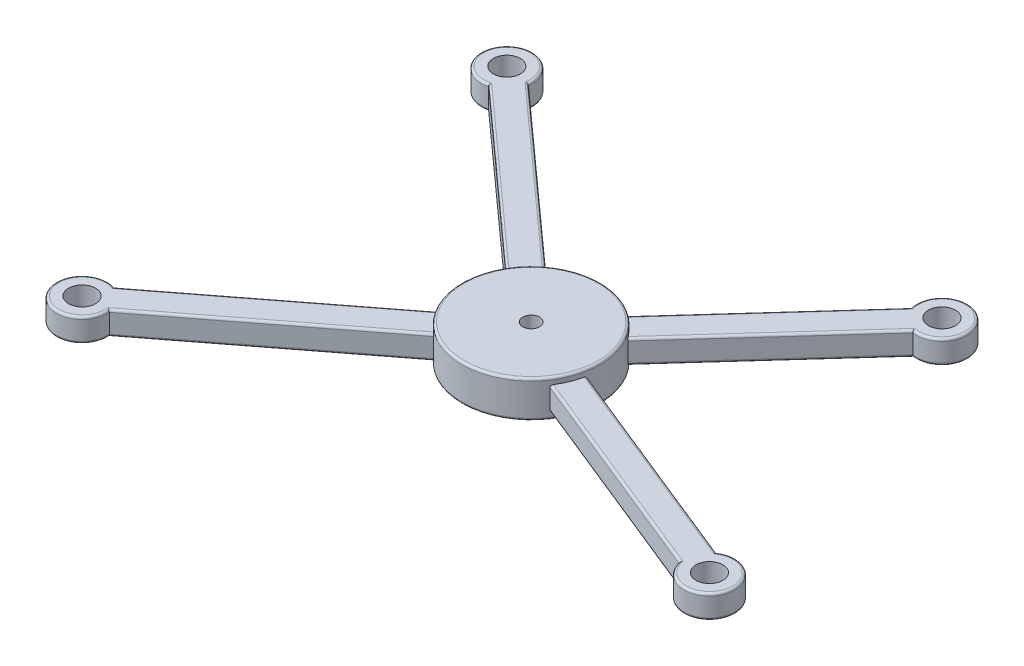
SolidWorks part; units mm, degrees
material "ABS"
ref_plane "Front Plane" through (0, 0, 0) normal (0, 0, 1) x (1, 0, 0)
ref_plane "Top Plane" through (0, 0, 0) normal (0, 1, 0) x (1, 0, 0)
ref_plane "Right Plane" through (0, 0, 0) normal (1, 0, 0) x (0, 0, -1)
sketch "Sketch1" plane through (0, 0, 0) normal (0, 1, 0) x (1, 0, 0)
  line L12 (-46.5941, 45.9944) -> (-0.2219, 4.3139)
  line L13 (36.9296, 45.3443) -> (-0.2219, 4.3139)
  line L14 (41.4662, 41.2365) -> (5.2085, 1.1933)
  line L15 (61.7716, -21.697) -> (5.2085, 1.1933)
  line L16 (59.4758, -27.3701) -> (0.4774, -3.4943)
  line L17 (-53.1887, -37.0871) -> (-4.7799, 0.1819)
  line L18 (-49.4552, -41.9365) -> (0.4774, -3.4943)
  line L19 (-50.6852, 41.4428) -> (-4.7799, 0.1819)
  arc A0 (-53.1887, -37.0871) -> (-49.4552, -41.9365) centre (-54.9671, -42.3181) ccw
  arc A1 (59.4758, -27.3701) -> (61.7716, -21.697) centre (64.888, -26.2593) ccw
  arc A2 (41.4662, 41.2365) -> (36.9296, 45.3443) centre (42.2856, 46.7004) ccw
  arc A3 (-46.5941, 45.9944) -> (-50.6852, 41.4428) centre (-52.0609, 46.7938) ccw
  dimension "D1" = 5.525
  dimension "D2" = 0.4774
  dimension "D3" = 5.2085
  dimension "D4" = 36.9296
  dimension "D5" = 41.4662
  dimension "D6" = 42.2856
  dimension "D7" = 59.4758
  dimension "D8" = 61.7716
  dimension "D9" = 64.888
  dimension "D10" = 0.2219
  dimension "D11" = 4.7799
  dimension "D12" = 46.5941
  dimension "D13" = 49.4552
  dimension "D14" = 50.6852
  dimension "D15" = 52.0609
  dimension "D16" = 53.1887
  dimension "D17" = 54.9671
  dimension "D18" = 0.1819
  dimension "D19" = 1.1933
  dimension "D20" = 4.3139
  dimension "D21" = 41.2365
  dimension "D22" = 41.4428
  dimension "D23" = 21.697
  dimension "D24" = 37.0871
  dimension "D27" = 3.4943
sketch "Sketch2" plane through (0, 0, 0) normal (0, 1, 0) x (1, 0, 0)
  circle A0 centre (0, 0) radius 15
  dimension "D1" = 30
extrude "Boss-Extrude1" add sketch "Sketch2" against normal mid plane 8
extrude "Boss-Extrude2" add sketch "Sketch1" along normal mid plane 5.11
fillet "Fillet1" radius 0.5 26 edges at (35.97, -2.555, 17.8576) (70.0095, -2.555, 28.3319) (38.2658, -2.555, 12.1846) (45.994, -2.555, -50.796) (26.7954, -2.555, -25.034) (22.2588, -2.555, -29.1417) (-27.7349, -2.555, -29.0433) (-56.17, -2.555, -50.4872) (0, -4, 15) (-31.826, -2.555, -24.4917) (-33.3455, -2.555, 21.8103) (-59.3449, -2.555, 45.6885) (-29.6121, -2.555, 26.6596) (0, 4, 15) (-33.3455, 2.555, 21.8103) (-59.3449, 2.555, 45.6885) (-29.6121, 2.555, 26.6596) (35.97, 2.555, 17.8576) (70.0095, 2.555, 28.3319) (38.2658, 2.555, 12.1846) (26.7954, 2.555, -25.034) (45.994, 2.555, -50.796) (22.2588, 2.555, -29.1417) (-27.7349, 2.555, -29.0433) (-56.17, 2.555, -50.4872) (-31.826, 2.555, -24.4917)
sketch "Sketch3" plane through (0, 4, 0) normal (0, 1, 0) x (1, 0, 0)
  circle A0 centre (0, 0) radius 1.825
  dimension "D1" = 3.65
extrude "Cut-Extrude1" cut sketch "Sketch3" against normal up to next
sketch "Sketch4" plane through (0, 2.555, 0) normal (0, 1, 0) x (1, 0, 0)
  circle A0 centre (-52.0609, 46.7938) radius 2.925
  circle A1 centre (42.2856, 46.7004) radius 2.925
  circle A2 centre (64.888, -26.2593) radius 2.925
  circle A3 centre (-54.9671, -42.3181) radius 2.925
  dimension "D1" = 5.85
extrude "Cut-Extrude2" cut sketch "Sketch4" against normal up to next
